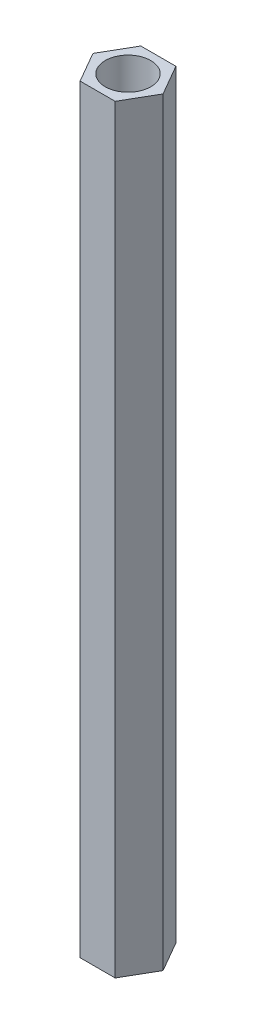
SolidWorks part; units mm, degrees
ref_plane "Front Plane" through (0, 0, 0) normal (0, 0, 1) x (1, 0, 0)
ref_plane "Top Plane" through (0, 0, 0) normal (0, 1, 0) x (1, 0, 0)
ref_plane "Right Plane" through (0, 0, 0) normal (1, 0, 0) x (0, 0, -1)
sketch "草图1" plane through (0, 0, 0) normal (0, 1, 0) x (1, 0, 0)
  line L1 (2.3094, 0) -> (1.1547, 2)
  line L2 (1.1547, 2) -> (-1.1547, 2)
  line L3 (-1.1547, 2) -> (-2.3094, 0)
  line L4 (-2.3094, 0) -> (-1.1547, -2)
  line L5 (-1.1547, -2) -> (1.1547, -2)
  line L6 (1.1547, -2) -> (2.3094, 0)
  circle A0 centre (0, 0) radius 2 construction
  dimension "D1" = 4
extrude "凸台-拉伸1" add sketch "草图1" along normal blind 50
sketch "草图2" plane through (0, 50, 0) normal (0, 1, 0) x (1, 0, 0)
  circle A0 centre (0, 0) radius 1.5
  dimension "D1" = 3
extrude "切除-拉伸1" cut sketch "草图2" against normal through all
